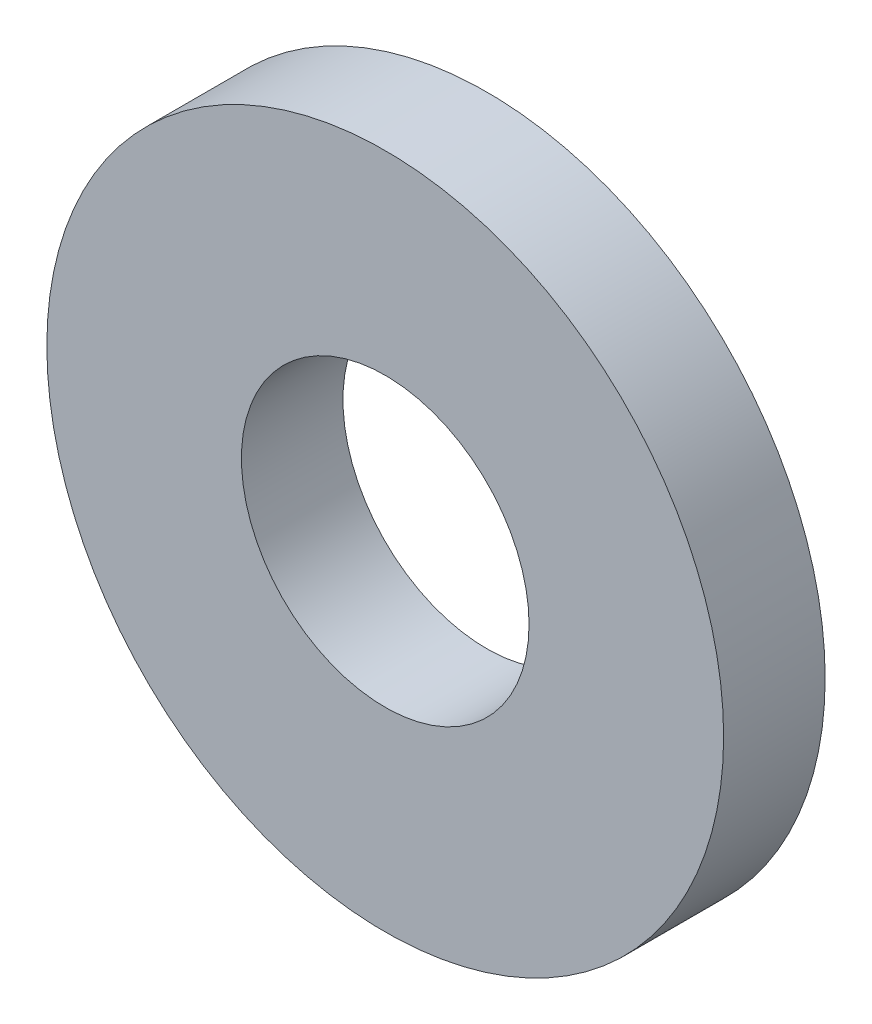
SolidWorks part; units mm, degrees
ref_plane "Alzado" through (0, 0, 0) normal (0, 0, 1) x (1, 0, 0)
ref_plane "Planta" through (0, 0, 0) normal (0, 1, 0) x (1, 0, 0)
ref_plane "Vista lateral" through (0, 0, 0) normal (1, 0, 0) x (0, 0, -1)
sketch "Croquis1" plane through (0, 0, 0) normal (0, 0, 1) x (1, 0, 0)
  circle A0 centre (0, 0) radius 4.25
  circle A1 centre (0, 0) radius 10
  dimension "D1" = 8.5
  dimension "D2" = 20
extrude "Saliente-Extruir1" add sketch "Croquis1" along normal blind 3
